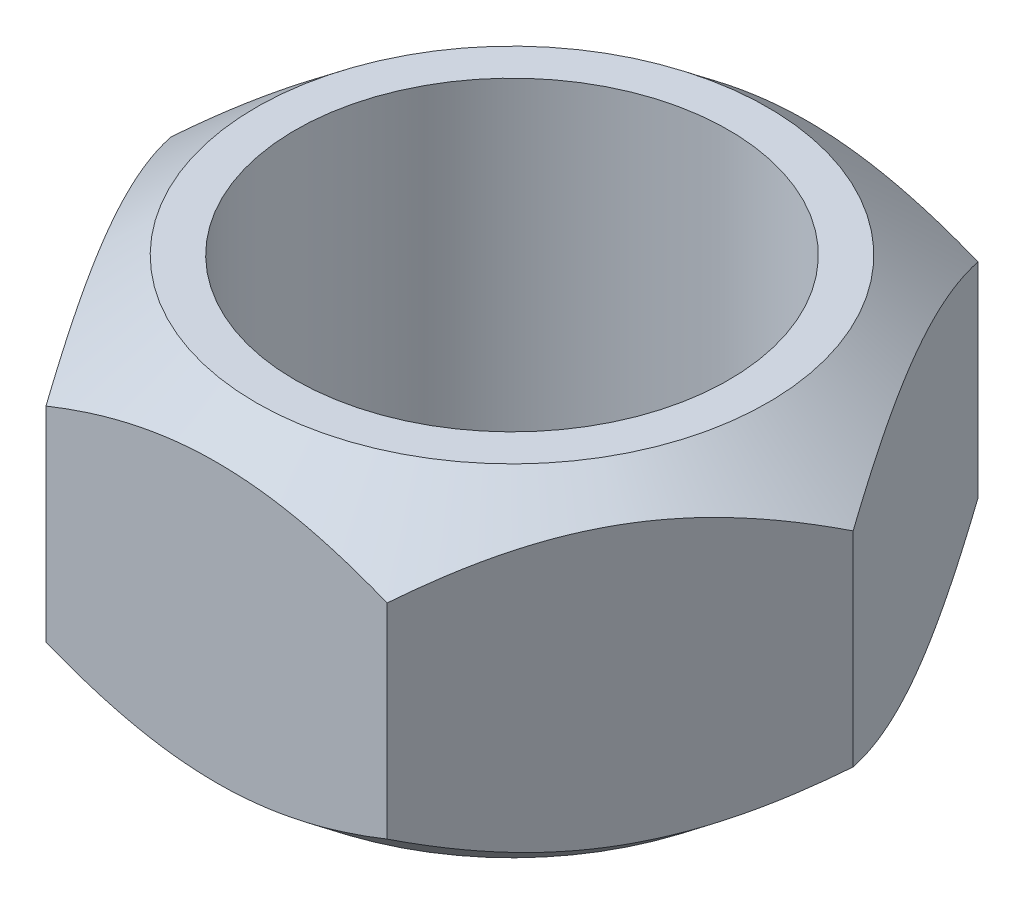
SolidWorks part; units mm, degrees
ref_plane "Front Plane" through (0, 0, 0) normal (0, 0, 1) x (1, 0, 0)
ref_plane "Top Plane" through (0, 0, 0) normal (0, 1, 0) x (1, 0, 0)
ref_plane "Right Plane" through (0, 0, 0) normal (1, 0, 0) x (0, 0, -1)
sketch "Sketch1" plane through (0, 0, 0) normal (0, 1, 0) x (1, 0, 0)
  line L1 (10, 0) -> (5, 8.6603)
  line L2 (5, 8.6603) -> (-5, 8.6603)
  line L3 (-5, 8.6603) -> (-10, 0)
  line L4 (-10, 0) -> (-5, -8.6603)
  line L5 (-5, -8.6603) -> (5, -8.6603)
  line L6 (5, -8.6603) -> (10, 0)
  circle A0 centre (0, 0) radius 8.6603 construction
  circle A1 centre (0, 0) radius 6.35
  dimension "D1" = 12.7
  dimension "D2" = 20
extrude "Boss-Extrude1" add sketch "Sketch1" along normal blind 10
cosmetic thread "Cosmetic Thread1" parameters "D2"=13.7
ref_axis "Axis1" through (0, 10, 0) along (0, -1, 0)
sketch "Sketch3" plane through (0, 0, 0) normal (0, 0, 1) x (1, 0, 0)
  line L0 (-10, 10) -> (-10, 7.9969)
  line L1 (-10, 10) -> (-10, 0) construction
  line L2 (-10, 7.9969) -> (-7.5, 10)
  line L3 (-10, 10) -> (-5, 10) construction
  line L4 (-7.5, 10) -> (-10, 10)
  point P8 (-10, 7.6047)
  point P9 (-7.5, 10)
  point P10 (-10, 7.9969)
revolve "Cut-Revolve1" cut sketch "Sketch3" angle 360 about axis through (0, 10, 0) along (0, -1, 0)
ref_plane "Plane1" through (0, 5, 0) normal (0, -1, 0) x (-1, 0, 0)
mirror "Mirror1" about plane through (0, 5, 0) normal (0, -1, 0) of "Cut-Revolve1"
